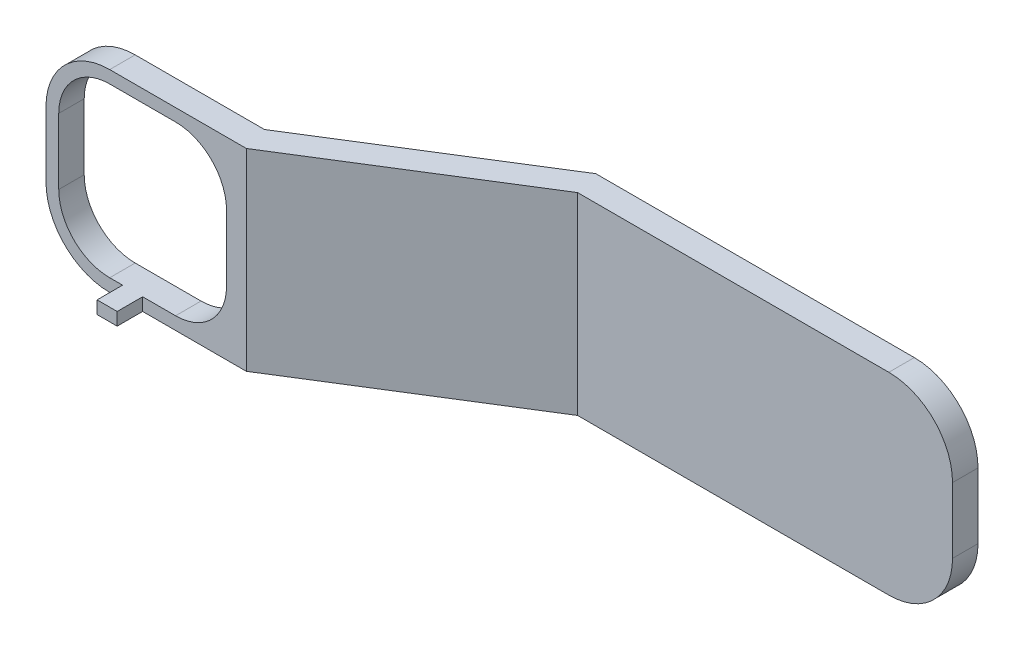
SolidWorks part; units mm, degrees
ref_plane "Front Plane" through (0, 0, 0) normal (0, 0, 1) x (1, 0, 0)
ref_plane "Top Plane" through (0, 0, 0) normal (0, 1, 0) x (1, 0, 0)
ref_plane "Right Plane" through (0, 0, 0) normal (1, 0, 0) x (0, 0, -1)
sketch "Sketch2" plane through (0, 0, 0) normal (0, 1, 0) x (1, 0, 0)
  line L0 (0, 0) -> (19.24, 0)
  line L1 (19.24, 0) -> (39.56, 12.7)
  line L2 (39.56, 12.7) -> (77.66, 12.7)
  dimension "D1" = 19.24
  dimension "D2" = 20.32
  dimension "D3" = 12.7
  dimension "D4" = 38.1
extrude "Extrude-Thin1" add sketch "Sketch2" along normal mid plane 19.24 thin
sketch "Sketch3" plane through (0, 0, 2.54) normal (0, 0, 1) x (1, 0, 0)
  line L0 (0, 9.62) -> (0, -9.62) construction
  line L1 (6.35, 8.3754) -> (12.9154, 8.3754)
  line L2 (1.27, 3.2954) -> (1.27, -3.27)
  line L3 (6.35, -8.35) -> (12.9154, -8.35)
  line L4 (17.9954, 3.2954) -> (17.9954, -3.27)
  line L6 (0, -9.62) -> (19.9685, -9.62) construction
  arc A0 (12.9154, -8.35) -> (17.9954, -3.27) centre (12.9154, -3.27) ccw
  arc A1 (1.27, -3.27) -> (6.35, -8.35) centre (6.35, -3.27) ccw
  arc A2 (12.9154, 8.3754) -> (17.9954, 3.2954) centre (12.9154, 3.2954) cw
  arc A3 (6.35, 8.3754) -> (1.27, 3.2954) centre (6.35, 3.2954) ccw
  point P8 (1.27, -8.35)
  point P11 (17.9954, 8.3754)
  point P14 (1.27, 8.3754)
  point P15 (1.27, 0.0127)
  dimension "D3" = 5.08
  dimension "D1" = 16.7254
  dimension "D2" = 16.7254
  dimension "D4" = 1.27
  dimension "D5" = 1.27
extrude "Cut-Extrude1" cut sketch "Sketch3" against normal through all
fillet "Fillet1" radius 6.35 4 edges at (77.66, -9.62, -11.43) (77.66, 9.62, -11.43) (0, -9.62, 1.27) (0, 9.62, 1.27)
sketch "Sketch4" plane through (0, 0, 2.54) normal (0, 0, 1) x (1, 0, 0)
  line L0 (6.35, -8.35) -> (12.9154, -8.35) construction
  line L1 (9.6327, -8.35) -> (7.6327, -8.35)
  line L2 (9.6327, -8.35) -> (9.6327, -9.62)
  line L3 (9.6327, -9.62) -> (7.6327, -9.62)
  line L4 (7.6327, -8.35) -> (7.6327, -9.62)
  line L5 (6.35, -9.62) -> (19.9685, -9.62) construction
  dimension "D1" = 2
extrude "Boss-Extrude1" add sketch "Sketch4" along normal blind 2.54
scale "Scale1" scale about centroid uniform scaling yes scale factor 2.54
